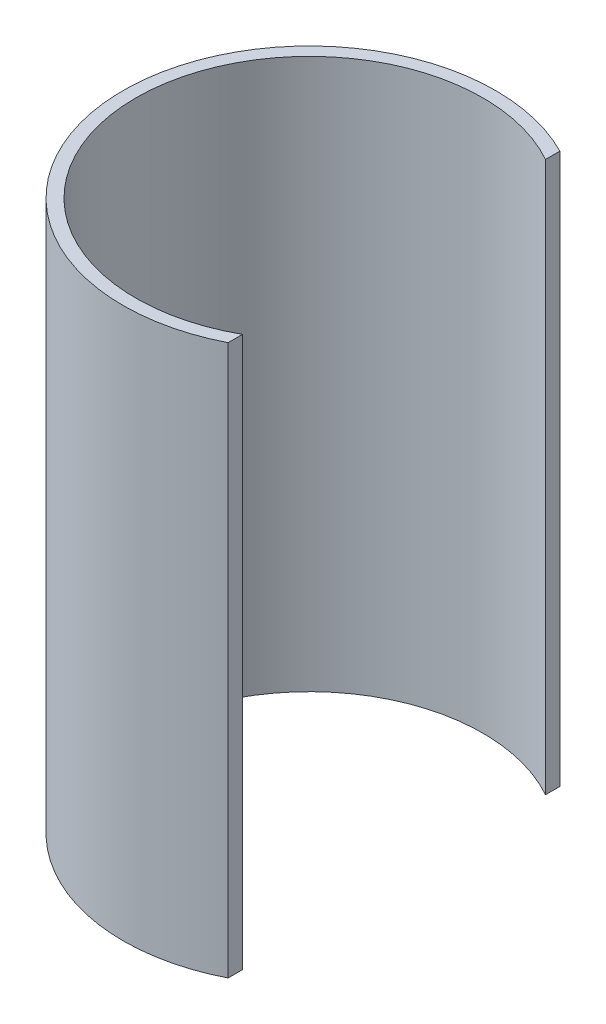
SolidWorks part; units mm, degrees
ref_plane "前视基准面" through (0, 0, 0) normal (0, 0, 1) x (1, 0, 0)
ref_plane "上视基准面" through (0, 0, 0) normal (0, 1, 0) x (1, 0, 0)
ref_plane "右视基准面" through (0, 0, 0) normal (1, 0, 0) x (0, 0, -1)
other "Configuration Table"
sketch "草图1" plane through (0, 0, 0) normal (0, 1, 0) x (1, 0, 0)
  line L0 (0, 52.8926) -> (0, -68.0992) construction
  line L1 (20, 39.1918) -> (20, 35.7911)
  line L2 (20, -35.7911) -> (20, -39.1918)
  arc A0 (20, 35.7911) -> (20, -35.7911) centre (0, 0) ccw
  arc A1 (20, 39.1918) -> (20, -39.1918) centre (0, 0) ccw
  dimension "D2" = 41
  dimension "D3" = 44
  dimension "D1" = 20
extrude "凸台-拉伸1" add sketch "草图1" along normal blind 130
